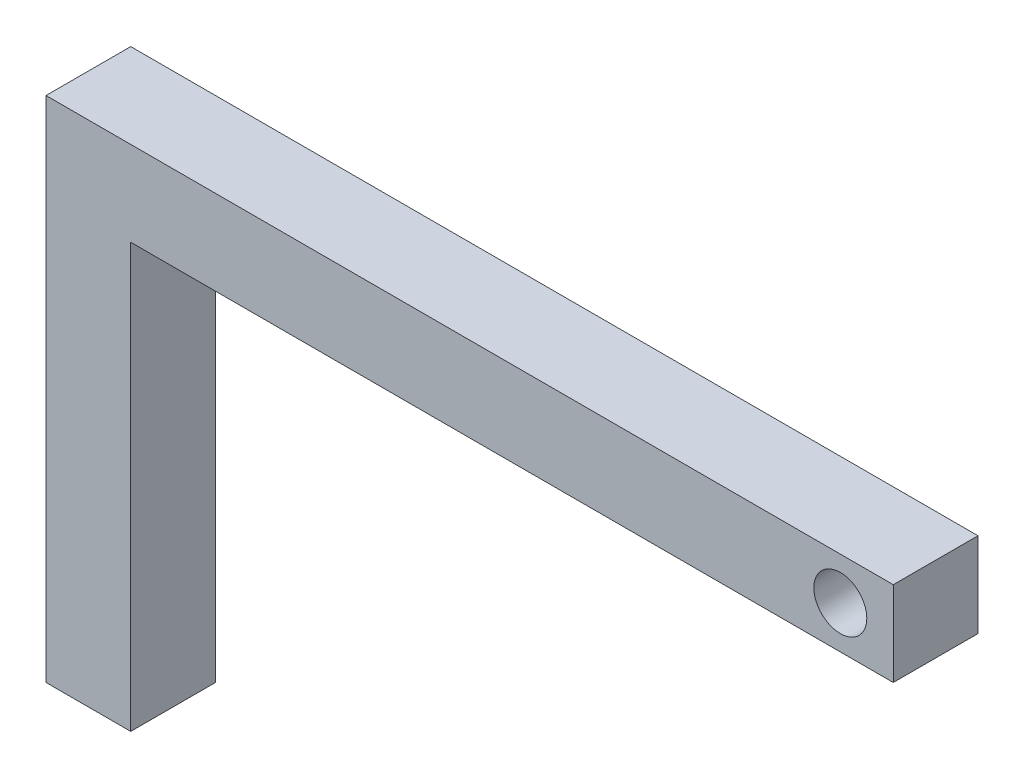
SolidWorks part; units mm, degrees
ref_plane "Front Plane" through (0, 0, 0) normal (0, 0, 1) x (1, 0, 0)
ref_plane "Top Plane" through (0, 0, 0) normal (0, 1, 0) x (1, 0, 0)
ref_plane "Right Plane" through (0, 0, 0) normal (1, 0, 0) x (0, 0, -1)
sketch "Sketch1" plane through (0, 0, 0) normal (0, 0, 1) x (1, 0, 0)
  line L0 (0, 892.9855) -> (0, 0) construction
  line L1 (0, 0) -> (1202.6614, 0) construction
  line L2 (0, 0) -> (0, 480)
  line L3 (0, 480) -> (800, 480)
  line L4 (800, 480) -> (800, 400)
  line L5 (800, 400) -> (80, 400)
  line L6 (80, 400) -> (80, 0)
  line L7 (80, 0) -> (0, 0)
  dimension "D1" = 800
  dimension "D3" = 80
  dimension "D4" = 80
  dimension "D5" = 400
extrude "Boss-Extrude1" add sketch "Sketch1" along normal blind 80
sketch "Sketch2" plane through (0, 0, 80) normal (0, 0, 1) x (1, 0, 0)
  line L0 (800, 440) -> (385.2259, 440) construction
  line L1 (800, 400) -> (800, 480) construction
  circle A0 centre (750, 440) radius 25
  dimension "D1" = 50
  dimension "D2" = 50
extrude "Cut-Extrude1" cut sketch "Sketch2" against normal blind 161
sketch "Sketch3" plane through (0, 0, 0) normal (0, -1, 0) x (1, 0, 0)
  line L0 (0, 40) -> (80, 40) construction
  line L1 (0, 80) -> (0, 0) construction
  line L2 (80, 80) -> (80, 0) construction
  circle A0 centre (40, 40) radius 15
  dimension "D1" = 30
extrude "Cut-Extrude2" cut sketch "Sketch3" against normal blind 10
